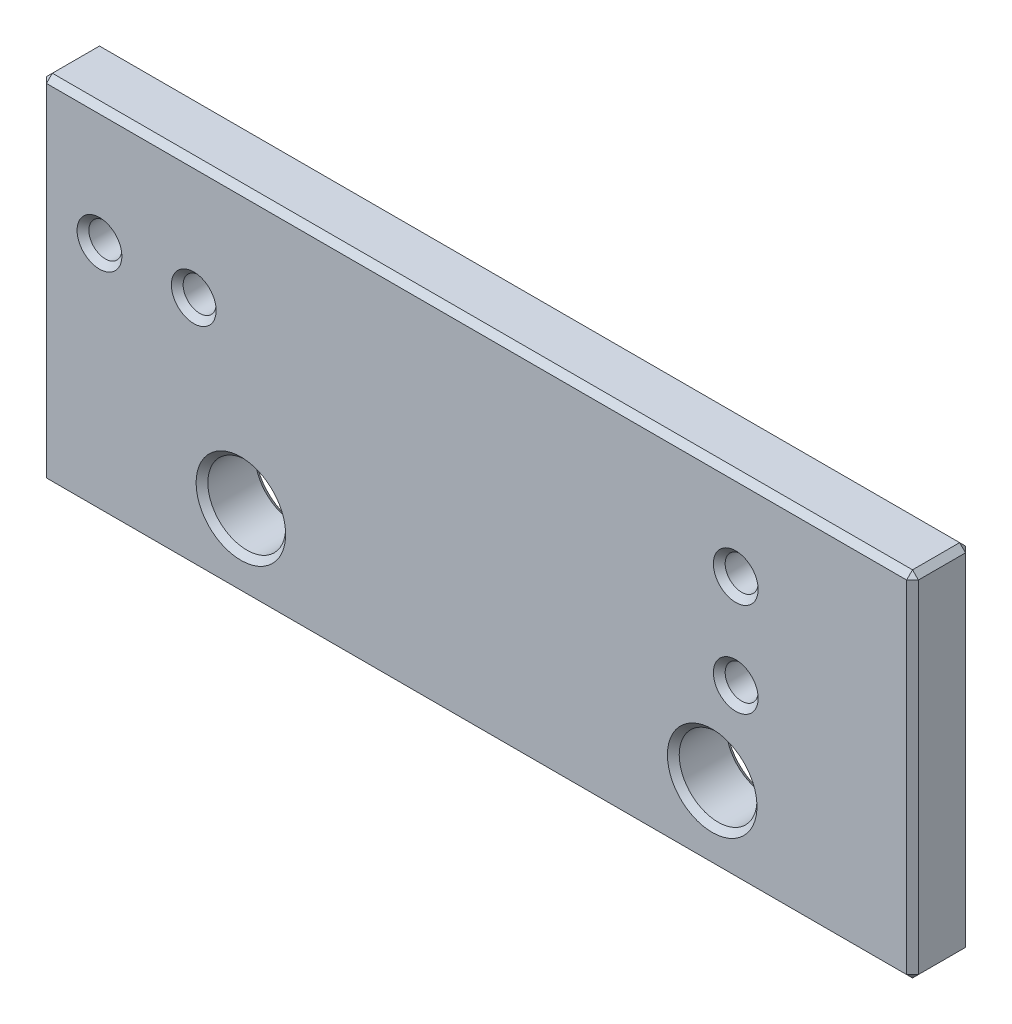
SolidWorks part; units mm, degrees
ref_plane "Top" through (0, 0, 0) normal (0, 0, 1) x (1, 0, 0)
ref_plane "Front" through (0, 0, 0) normal (0, 1, 0) x (1, 0, 0)
ref_plane "Right" through (0, 0, 0) normal (1, 0, 0) x (0, 0, -1)
sketch "Sketch1" plane through (0, 0, 0) normal (0, 0, 1) x (1, 0, 0)
  line L1 (0, 0) -> (74, 0)
  line L2 (0, 0) -> (0, 30)
  line L3 (0, 30) -> (74, 30)
  line L4 (74, 0) -> (74, 30)
  dimension "D1" = 30
  dimension "D2" = 74
extrude "Boss-Extrude1" add sketch "Sketch1" along normal blind 5
sketch "Sketch2" plane through (0, 0, 5) normal (0, 0, 1) x (1, 0, 0)
  line L0 (17, 6.5) -> (57, 6.5)
  line L1 (0, 0) -> (74, 0) construction
  line L2 (74, 0) -> (74, 30) construction
  dimension "D1" = 6.5
  dimension "D2" = 40
  dimension "D3" = 17
hole_wizard "M6 Clearance Hole1" positions "Sketch3" profile "Sketch4" hole size "M6" standard "DIN" end condition through all
sketch "Sketch3" plane through (0, 0, 5) normal (0, 0, 1) x (1, 0, 0)
  point P0 (17, 6.5)
  point P3 (57, 6.5)
sketch "Sketch4" plane through (17, 6.5, 5) normal (1, 0, 0) x (0, -1, 0)
  line L0 (0, 0) -> (0, 5)
  line L1 (0, 5) -> (3.3, 5)
  line L2 (3.3, 5) -> (3.3, 0)
  line L5 (3.3, 0) -> (0, 0)
  line L11 (0, -6.35) -> (0, 107.95) construction
  dimension "Thru Hole Dia." = 6.6
  dimension "Thru Hole Depth" = 5
sketch "Sketch5" plane through (0, 0, 5) normal (0, 0, 1) x (1, 0, 0)
  line L0 (59, 14.5) -> (59, 22.5) construction
  line L1 (74, 0) -> (74, 30) construction
  line L2 (74, 30) -> (0, 30) construction
  circle A0 centre (59, 22.5) radius 1.4
  circle A1 centre (59, 14.5) radius 1.4
  dimension "D4" = 2.8
  dimension "D1" = 8
  dimension "D2" = 15
  dimension "D3" = 7.5
extrude "Cut-Extrude1" cut sketch "Sketch5" against normal blind 5
sketch "Sketch6" plane through (0, 0, 5) normal (0, 0, 1) x (1, 0, 0)
  line L0 (5, 20) -> (13, 20) construction
  line L1 (74, 30) -> (0, 30) construction
  line L2 (0, 30) -> (0, 0) construction
  circle A0 centre (5, 20) radius 1.4
  circle A1 centre (13, 20) radius 1.4
  dimension "D4" = 2.8
  dimension "D1" = 8
  dimension "D2" = 10
  dimension "D3" = 5
extrude "Cut-Extrude2" cut sketch "Sketch6" against normal blind 5
chamfer "Chamfer1" distance 0.5 angle 45 24 edges at (60.3, 6.5, 0) (20.3, 6.5, 0) (60.4, 14.5, 0) (60.4, 22.5, 0) (14.4, 20, 0) (6.4, 20, 0) (60.3, 6.5, 5) (20.3, 6.5, 5) (60.4, 14.5, 5) (60.4, 22.5, 5) (14.4, 20, 5) (6.4, 20, 5) (37, 0, 0) (74, 15, 0) (37, 30, 0) (0, 15, 0) (37, 30, 5) (74, 30, 2.5) (74, 15, 5) (74, 0, 2.5) (37, 0, 5) (0, 30, 2.5) (0, 15, 5) (0, 0, 2.5)
